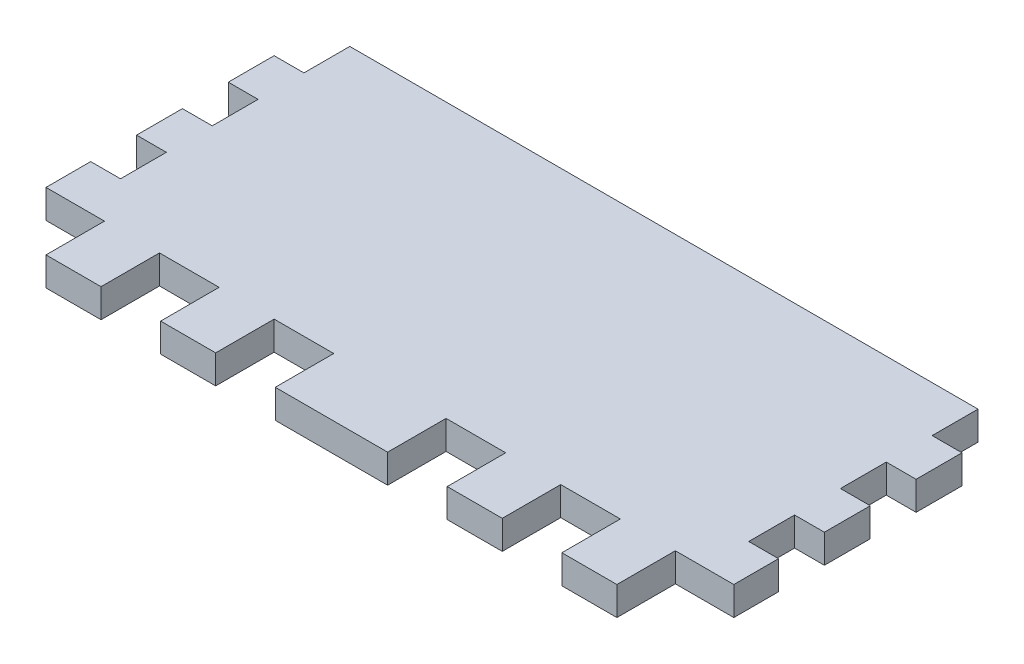
SolidWorks part; units mm, degrees
ref_plane "Front Plane" through (0, 0, 0) normal (0, 0, 1) x (1, 0, 0)
ref_plane "Top Plane" through (0, 0, 0) normal (0, 1, 0) x (1, 0, 0)
ref_plane "Right Plane" through (0, 0, 0) normal (1, 0, 0) x (0, 0, -1)
sketch "Sketch1" plane through (0, 0, 0) normal (0, 1, 0) x (1, 0, 0)
  line L1 (-38.1, -15.24) -> (38.1, -15.24)
  line L2 (-38.1, -15.24) -> (-38.1, 15.24)
  line L3 (-38.1, 15.24) -> (38.1, 15.24)
  line L4 (38.1, -15.24) -> (38.1, 15.24)
  line L5 (-38.1, -15.24) -> (38.1, 15.24) construction
  line L6 (-38.1, 15.24) -> (38.1, -15.24) construction
  point P0 (0, 0)
  dimension "D1" = 76.2
  dimension "D2" = 30.48
extrude "Boss-Extrude1" add sketch "Sketch1" along normal blind 3.175
sketch "Sketch2" plane through (0, 0, 0) normal (0, -1, 0) x (1, 0, 0)
  circle A0 centre (0, 0) radius 6.8807
sketch "Sketch5" plane through (0, 3.175, 0) normal (0, 1, 0) x (1, 0, 0)
  line L0 (-38.1, 5.08) -> (-34.798, 5.08)
  line L1 (-38.1, 15.24) -> (-34.798, 15.24)
  line L2 (-38.1, 15.24) -> (-38.1, 10.16)
  line L3 (-38.1, 10.16) -> (-34.798, 10.16)
  line L4 (-34.798, 15.24) -> (-34.798, 10.16)
  line L5 (-38.1, 15.24) -> (-34.798, 10.16) construction
  line L6 (-38.1, 10.16) -> (-34.798, 15.24) construction
  line L7 (-38.1, 5.08) -> (-38.1, 0)
  line L8 (-38.1, 0) -> (-34.798, 0)
  line L9 (-34.798, 5.08) -> (-34.798, 0)
  line L10 (-38.1, 5.08) -> (-34.798, 0) construction
  line L11 (-38.1, 0) -> (-34.798, 5.08) construction
  line L12 (-38.1, -5.08) -> (-34.798, -5.08)
  line L13 (-38.1, -5.08) -> (-38.1, -10.16)
  line L14 (-38.1, -10.16) -> (-34.798, -10.16)
  line L15 (-34.798, -5.08) -> (-34.798, -10.16)
  line L16 (-38.1, -5.08) -> (-34.798, -10.16) construction
  line L17 (-38.1, -10.16) -> (-34.798, -5.08) construction
  line L18 (0, 0) -> (0, 15.24) construction
  line L19 (38.1, 15.24) -> (-38.1, 15.24) construction
  line L20 (38.1, -10.16) -> (34.798, -5.08) construction
  line L21 (38.1, -5.08) -> (34.798, -10.16) construction
  line L22 (38.1, 0) -> (34.798, 5.08) construction
  line L23 (38.1, 5.08) -> (34.798, 0) construction
  line L24 (38.1, 10.16) -> (34.798, 15.24) construction
  line L25 (38.1, 15.24) -> (34.798, 10.16) construction
  line L26 (34.798, -5.08) -> (34.798, -10.16)
  line L27 (38.1, -10.16) -> (34.798, -10.16)
  line L28 (38.1, -5.08) -> (38.1, -10.16)
  line L29 (38.1, -5.08) -> (34.798, -5.08)
  line L30 (34.798, 5.08) -> (34.798, 0)
  line L31 (38.1, 0) -> (34.798, 0)
  line L32 (38.1, 5.08) -> (38.1, 0)
  line L33 (34.798, 15.24) -> (34.798, 10.16)
  line L34 (38.1, 10.16) -> (34.798, 10.16)
  line L35 (38.1, 15.24) -> (38.1, 10.16)
  line L36 (38.1, 15.24) -> (34.798, 15.24)
  line L37 (38.1, 5.08) -> (34.798, 5.08)
  point P4 (-36.449, 12.7)
  point P11 (-36.449, 2.54)
  point P16 (-36.449, -7.62)
  point P34 (36.449, -7.62)
  point P35 (36.449, 2.54)
  point P36 (36.449, 12.7)
  dimension "D1" = 3.302
  dimension "D2" = 5.08
  dimension "D3" = 3
extrude "Cut-Extrude2" cut sketch "Sketch5" against normal through all
sketch "Sketch6" plane through (0, 3.175, 0) normal (0, 1, 0) x (1, 0, 0)
  line L0 (38.1, -15.24) -> (38.1, -10.16) construction
  line L1 (-38.1, -15.24) -> (38.1, -15.24)
  line L2 (-38.1, -15.24) -> (-38.1, -21.59)
  line L3 (-38.1, -21.59) -> (38.1, -21.59)
  line L4 (38.1, -15.24) -> (38.1, -21.59)
  line L5 (-38.1, -15.24) -> (38.1, -21.59) construction
  line L6 (-38.1, -21.59) -> (38.1, -15.24) construction
  point P4 (0, -18.415)
  dimension "D1" = 6.35
extrude "Boss-Extrude3" add sketch "Sketch6" against normal up to surface (3.175 mm away) up to face at (0, 0, 0)
sketch "Sketch7" plane through (0, 3.175, 0) normal (0, 1, 0) x (1, 0, 0)
  line L1 (-38.227, -21.717) -> (-31.623, -21.717)
  line L2 (-38.227, -21.717) -> (-38.227, -15.113)
  line L3 (-38.227, -15.113) -> (-31.623, -15.113)
  line L4 (-31.623, -21.717) -> (-31.623, -15.113)
  line L5 (-38.227, -21.717) -> (-31.623, -15.113) construction
  line L6 (-38.227, -15.113) -> (-31.623, -21.717) construction
  line L8 (-25.527, -21.717) -> (-18.923, -21.717)
  line L9 (-25.527, -21.717) -> (-25.527, -15.113)
  line L10 (-25.527, -15.113) -> (-18.923, -15.113)
  line L11 (-18.923, -21.717) -> (-18.923, -15.113)
  line L12 (-25.527, -21.717) -> (-18.923, -15.113) construction
  line L13 (-25.527, -15.113) -> (-18.923, -21.717) construction
  line L14 (-12.827, -21.717) -> (-6.223, -21.717)
  line L15 (-12.827, -21.717) -> (-12.827, -15.113)
  line L16 (-12.827, -15.113) -> (-6.223, -15.113)
  line L17 (-6.223, -21.717) -> (-6.223, -15.113)
  line L18 (-12.827, -21.717) -> (-6.223, -15.113) construction
  line L19 (-12.827, -15.113) -> (-6.223, -21.717) construction
  line L20 (0, 0) -> (0, 15.24) construction
  line L21 (34.798, 15.24) -> (-34.798, 15.24) construction
  line L22 (12.827, -15.113) -> (6.223, -21.717) construction
  line L23 (12.827, -21.717) -> (6.223, -15.113) construction
  line L24 (25.527, -15.113) -> (18.923, -21.717) construction
  line L25 (25.527, -21.717) -> (18.923, -15.113) construction
  line L26 (38.227, -15.113) -> (31.623, -21.717) construction
  line L27 (38.227, -21.717) -> (31.623, -15.113) construction
  line L28 (6.223, -21.717) -> (6.223, -15.113)
  line L29 (12.827, -15.113) -> (6.223, -15.113)
  line L30 (12.827, -21.717) -> (12.827, -15.113)
  line L31 (12.827, -21.717) -> (6.223, -21.717)
  line L32 (18.923, -21.717) -> (18.923, -15.113)
  line L33 (25.527, -15.113) -> (18.923, -15.113)
  line L34 (25.527, -21.717) -> (25.527, -15.113)
  line L35 (25.527, -21.717) -> (18.923, -21.717)
  line L36 (31.623, -21.717) -> (31.623, -15.113)
  line L37 (38.227, -15.113) -> (31.623, -15.113)
  line L38 (38.227, -21.717) -> (38.227, -15.113)
  line L39 (38.227, -21.717) -> (31.623, -21.717)
  point P4 (-34.925, -18.415)
  point P14 (-22.225, -18.415)
  point P19 (-9.525, -18.415)
  point P36 (9.525, -18.415)
  point P37 (22.225, -18.415)
  point P38 (34.925, -18.415)
  dimension "D1" = 6.604
  dimension "D2" = 6.604
  dimension "D4" = 18.415
  dimension "D5" = 34.925
  dimension "D3" = 3
extrude "Cut-Extrude3" cut sketch "Sketch7" against normal through all
